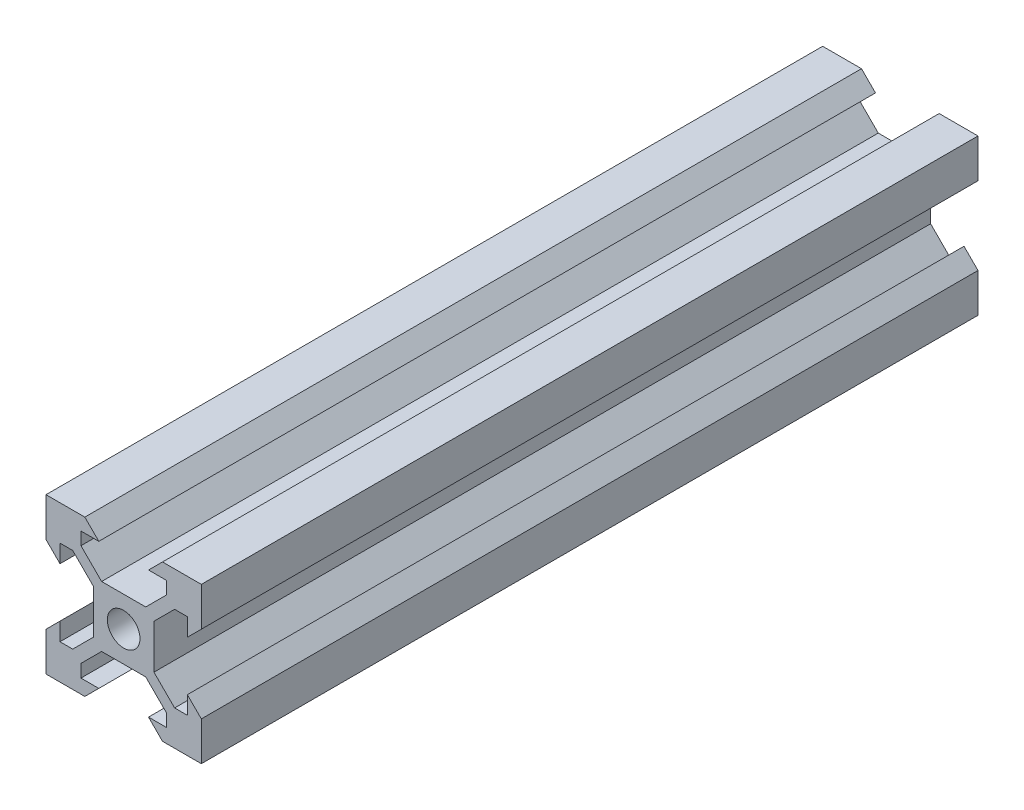
SolidWorks part; units mm, degrees
ref_plane "Front Plane" through (0, 0, 0) normal (0, 0, 1) x (1, 0, 0)
ref_plane "Top Plane" through (0, 0, 0) normal (0, 1, 0) x (1, 0, 0)
ref_plane "Right Plane" through (0, 0, 0) normal (1, 0, 0) x (0, 0, -1)
sketch "Sketch1" plane through (0, 0, 0) normal (0, 0, 1) x (1, 0, 0)
  line L0 (-10, 10) -> (-10, 5)
  line L1 (-10, 5) -> (-8.2, 3.2)
  line L2 (-8.2, 3.2) -> (-8.2, 5.4993)
  line L3 (-8.2, 5.4993) -> (-6.56, 5.4993)
  line L4 (-6.56, 5.4993) -> (-3.9007, 2.84)
  line L5 (-3.9007, 2.84) -> (-3.9007, -2.84)
  line L6 (-3.9007, -2.84) -> (-6.56, -5.4993)
  line L7 (-6.56, -5.4993) -> (-8.2, -5.4993)
  line L8 (-8.2, -5.4993) -> (-8.2, -3.2)
  line L9 (-8.2, -3.2) -> (-10, -5)
  line L10 (-10, -5) -> (-10, -10)
  line L11 (-10, -10) -> (-5, -10)
  line L12 (-5, -10) -> (-3.2, -8.2)
  line L13 (-3.2, -8.2) -> (-5.4993, -8.2)
  line L14 (-5.4993, -8.2) -> (-5.4993, -6.56)
  line L15 (-5.4993, -6.56) -> (-2.84, -3.9007)
  line L16 (-2.84, -3.9007) -> (2.84, -3.9007)
  line L17 (2.84, -3.9007) -> (5.4993, -6.56)
  line L18 (5.4993, -6.56) -> (5.4993, -8.2)
  line L19 (5.4993, -8.2) -> (3.2, -8.2)
  line L20 (3.2, -8.2) -> (5, -10)
  line L21 (5, -10) -> (10, -10)
  line L22 (10, -10) -> (10, -5)
  line L23 (10, -5) -> (8.2, -3.2)
  line L24 (8.2, -3.2) -> (8.2, -5.4993)
  line L25 (8.2, -5.4993) -> (6.56, -5.4993)
  line L26 (6.56, -5.4993) -> (3.9007, -2.84)
  line L27 (3.9007, -2.84) -> (3.9007, 2.84)
  line L28 (3.9007, 2.84) -> (6.56, 5.4993)
  line L29 (6.56, 5.4993) -> (8.2, 5.4993)
  line L30 (8.2, 5.4993) -> (8.2, 3.2)
  line L31 (8.2, 3.2) -> (10, 5)
  line L32 (10, 5) -> (10, 10)
  line L33 (10, 10) -> (5, 10)
  line L34 (5, 10) -> (3.2, 8.2)
  line L35 (3.2, 8.2) -> (5.4993, 8.2)
  line L36 (5.4993, 8.2) -> (5.4993, 6.56)
  line L37 (5.4993, 6.56) -> (2.84, 3.9007)
  line L38 (2.84, 3.9007) -> (-2.84, 3.9007)
  line L39 (-2.84, 3.9007) -> (-5.4993, 6.56)
  line L40 (-5.4993, 6.56) -> (-5.4993, 8.2)
  line L41 (-5.4993, 8.2) -> (-3.2, 8.2)
  line L42 (-3.2, 8.2) -> (-5, 10)
  line L43 (-5, 10) -> (-10, 10)
  circle A0 centre (0, 0) radius 2.1
extrude "Boss-Extrude1" add sketch "Sketch1" against normal blind 500
sketch "草图1" plane through (0, 0, 0) normal (0, 0, 1) x (1, 0, 0)
  line L1 (-13.9529, 12.8384) -> (13.9529, 12.8384)
  line L2 (-13.9529, 12.8384) -> (-13.9529, -12.8384)
  line L3 (-13.9529, -12.8384) -> (13.9529, -12.8384)
  line L4 (13.9529, 12.8384) -> (13.9529, -12.8384)
  line L5 (-13.9529, 12.8384) -> (13.9529, -12.8384) construction
  line L6 (-13.9529, -12.8384) -> (13.9529, 12.8384) construction
  point P0 (0, 0)
extrude "切除-拉伸1" cut sketch "草图1" against normal blind 400
